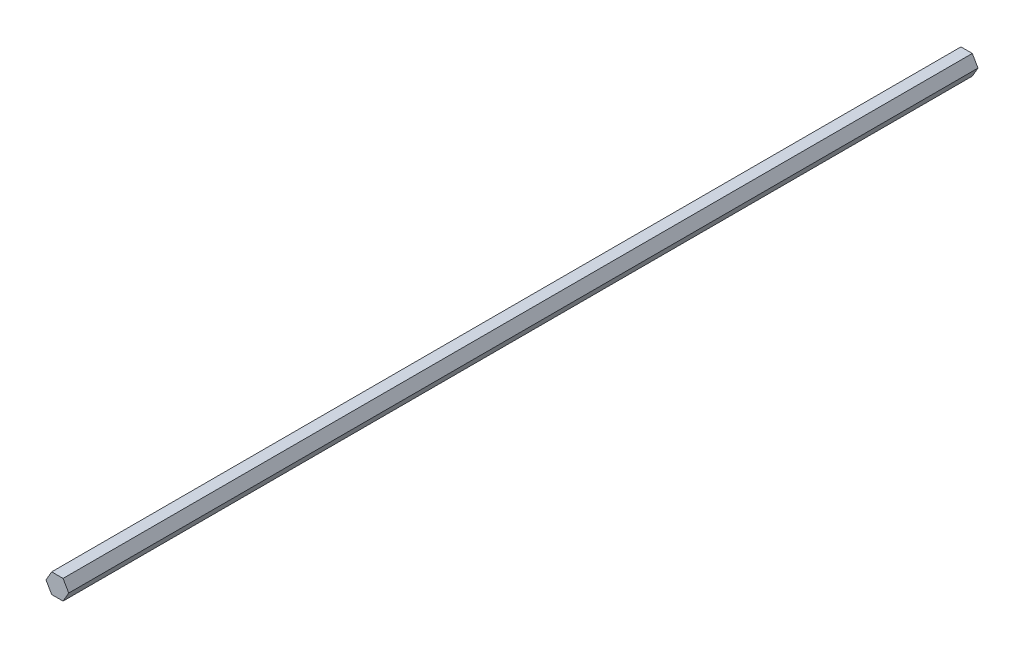
SolidWorks part; units mm, degrees
material "5052-H32"
ref_plane "Front Plane" through (0, 0, 0) normal (0, 0, 1) x (1, 0, 0)
ref_plane "Top Plane" through (0, 0, 0) normal (0, 1, 0) x (1, 0, 0)
ref_plane "Right Plane" through (0, 0, 0) normal (1, 0, 0) x (0, 0, -1)
sketch "Sketch 1" plane through (0, 0, 0) normal (0, 0, 1) x (1, 0, 0)
  line L1 (7.3025, 0) -> (3.6512, 6.3242)
  line L2 (3.6512, 6.3242) -> (-3.6512, 6.3242)
  line L3 (-3.6512, 6.3242) -> (-7.3025, 0)
  line L4 (-7.3025, 0) -> (-3.6513, -6.3242)
  line L5 (-3.6513, -6.3242) -> (3.6512, -6.3242)
  line L6 (3.6512, -6.3242) -> (7.3025, 0)
  circle A0 centre (0, 0) radius 6.3242 construction
  dimension "D1" = 7.3025
extrude "Boss-Extrude1" add sketch "Sketch 1" along normal mid plane 584.2
